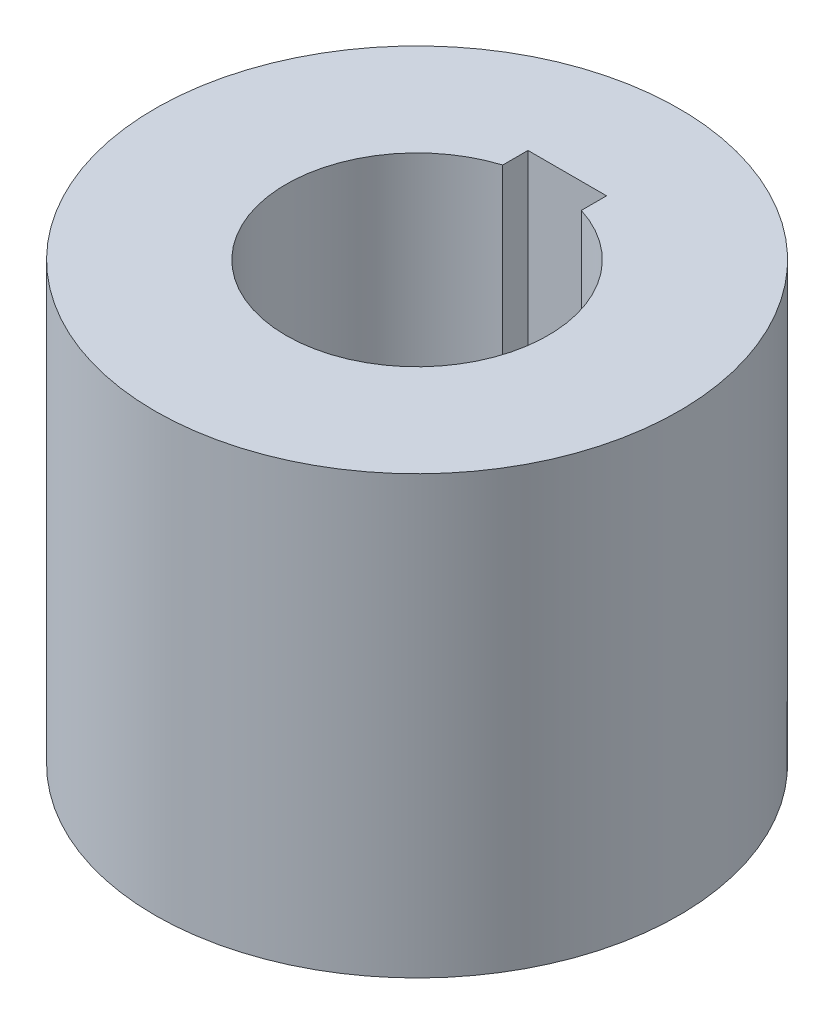
SolidWorks part; units mm, degrees
ref_plane "Front Plane" through (0, 0, 0) normal (0, 0, 1) x (1, 0, 0)
ref_plane "Top Plane" through (0, 0, 0) normal (0, 1, 0) x (1, 0, 0)
ref_plane "Right Plane" through (0, 0, 0) normal (1, 0, 0) x (0, 0, -1)
sketch "Sketch2" plane through (0, 0, 0) normal (0, 1, 0) x (1, 0, 0)
  circle A0 centre (0, 0) radius 60
  dimension "D1" = 120
extrude "Boss-Extrude1" add sketch "Sketch2" along normal blind 100
sketch "Sketch3" plane through (0, 100, 0) normal (0, 1, 0) x (1, 0, 0)
  circle A0 centre (0, 0) radius 30
  dimension "D1" = 60
extrude "Cut-Extrude1" cut sketch "Sketch3" against normal through all
sketch "Sketch4" plane through (0, 100, 0) normal (0, 1, 0) x (1, 0, 0)
  line L1 (-9, 34.4) -> (9, 34.4)
  line L2 (-9, 34.4) -> (-9, 23.4)
  line L3 (-9, 23.4) -> (9, 23.4)
  line L4 (9, 34.4) -> (9, 23.4)
  line L5 (-9, 34.4) -> (9, 23.4) construction
  line L6 (-9, 23.4) -> (9, 34.4) construction
  point P0 (0, 28.9)
  point P5 (0, 31.7609)
  point P7 (0, 30)
  point P9 (0, 30)
  point P10 (0, 0)
  dimension "D1" = 18
  dimension "D2" = 11
  dimension "D3" = 34.4
extrude "Cut-Extrude2" cut sketch "Sketch4" against normal through all
